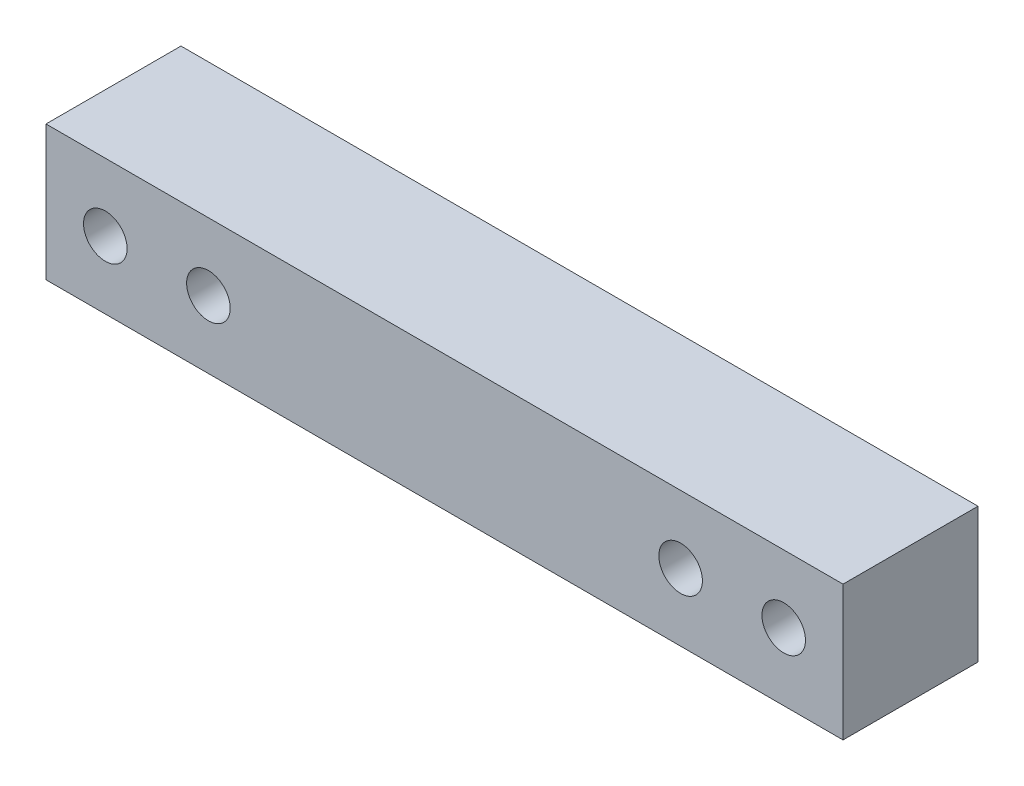
SolidWorks part; units mm, degrees
ref_plane "Front Plane" through (0, 0, 0) normal (0, 0, 1) x (1, 0, 0)
ref_plane "Top Plane" through (0, 0, 0) normal (0, 1, 0) x (1, 0, 0)
ref_plane "Right Plane" through (0, 0, 0) normal (1, 0, 0) x (0, 0, -1)
sketch "Sketch1" plane through (0, 0, 0) normal (0, 1, 0) x (1, 0, 0)
  line L0 (-58.5761, 0) -> (16.4239, 0)
  line L1 (16.4239, 0) -> (16.4239, 5)
  line L2 (16.4239, 5) -> (-37.7115, 5)
  line L3 (-37.7115, 5) -> (-37.7115, 10)
  line L4 (-58.5761, 0) -> (-58.5761, 10)
  line L5 (-58.5761, 10) -> (-37.7115, 10)
  dimension "D1" = 75
  dimension "D2" = 10
  dimension "D3" = 5
extrude "Boss-Extrude1" add sketch "Sketch1" along normal blind 12.7
sketch "Sketch2" plane through (0, 0, -10) normal (0, 0, -1) x (-1, 0, 0)
  line L0 (58.5761, 6.35) -> (37.7115, 6.35)
  line L1 (58.5761, 12.7) -> (58.5761, 0) construction
  line L2 (37.7115, 12.7) -> (37.7115, 0) construction
  line L3 (41.2438, 6.35) -> (41.2438, 0)
  line L4 (37.7115, 0) -> (58.5761, 0) construction
  line L5 (55.0438, 1.6197) -> (58.5761, 1.6197)
  line L6 (55.0438, 6.35) -> (55.0438, 0)
  line L7 (37.7115, 2.551) -> (41.2438, 2.551)
  line L8 (37.7115, 12.7) -> (37.7115, 0) construction
  circle A0 centre (43.2938, 6.35) radius 2.05
  circle A1 centre (52.9938, 6.35) radius 2.05
  dimension "D1" = 4.1
  dimension "D2" = 13.8
extrude "Cut-Extrude1" cut sketch "Sketch2" against normal blind 12.7 contours L0 A0 | L0 A0 | L0 A1 | L0 A1
sketch "Sketch3" plane through (0, 0, 0) normal (0, 0, 1) x (1, 0, 0)
  line L0 (-58.5761, 12.7) -> (16.4239, 12.7)
  line L1 (16.4239, 12.7) -> (16.4239, 0)
  line L2 (16.4239, 0) -> (-58.5761, 0)
  line L3 (-58.5761, 0) -> (-58.5761, 12.7)
  circle A0 centre (-52.9938, 6.35) radius 2.05
  circle A1 centre (-43.2938, 6.35) radius 2.05
extrude "Boss-Extrude3" add sketch "Sketch3" against normal blind 12.7
sketch "Sketch4" plane through (0, 0, -12.7) normal (0, 0, -1) x (-1, 0, 0)
  line L4 (-16.4239, 12.7) -> (58.5761, 12.7) construction
  line L6 (21.0761, 0) -> (21.0761, 12.7)
  line L7 (58.5761, 0) -> (-16.4239, 0) construction
  circle A4 centre (43.2938, 6.35) radius 2.05
  circle A5 centre (52.9938, 6.35) radius 2.05
  circle A6 centre (-1.1415, 6.35) radius 2.05
  circle A7 centre (-10.8415, 6.35) radius 2.05
extrude "Cut-Extrude2" cut sketch "Sketch4" against normal blind 21.7 contours A7 | A6
